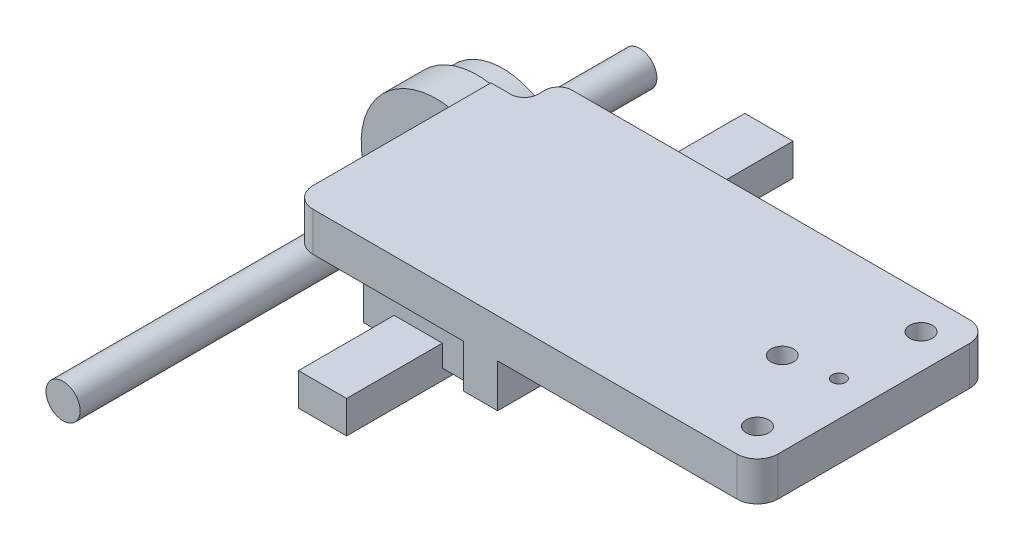
SolidWorks part; units mm, degrees
ref_plane "Front Plane" through (0, 0, 0) normal (0, 0, 1) x (1, 0, 0)
ref_plane "Top Plane" through (0, 0, 0) normal (0, 1, 0) x (1, 0, 0)
ref_plane "Right Plane" through (0, 0, 0) normal (1, 0, 0) x (0, 0, -1)
sketch "Sketch1" plane through (0, 0, 0) normal (0, 1, 0) x (1, 0, 0)
  line L0 (-36.9824, 21.6027) -> (-36.9824, -21.6027)
  line L1 (-43.18, 21.6027) -> (39.37, 21.6027)
  line L2 (-43.18, 21.6027) -> (-43.18, -17.7927)
  line L3 (-39.37, -21.6027) -> (39.37, -21.6027)
  line L4 (43.18, 17.7927) -> (43.18, -17.7927)
  line L5 (-43.18, 21.6027) -> (43.18, -21.6027) construction
  line L6 (-43.18, -21.6027) -> (43.18, 21.6027) construction
  line L7 (-43.18, 15.2527) -> (-36.9824, 15.2527)
  arc A0 (-39.37, -21.6027) -> (-43.18, -17.7927) centre (-39.37, -17.7927) cw
  arc A1 (43.18, -17.7927) -> (39.37, -21.6027) centre (39.37, -17.7927) cw
  arc A2 (39.37, 21.6027) -> (43.18, 17.7927) centre (39.37, 17.7927) cw
  point P1 (0, 0)
  dimension "D3" = 3.81
  dimension "D1" = 43.2054
  dimension "D2" = 86.36
  dimension "D4" = 80.1624
  dimension "D5" = 6.35
extrude "Boss-Extrude1" add sketch "Sketch1" along normal blind 7.2517 contours A2 L1 L0 L3 A1 L4 | A0 L3 L0 L7 L2
fillet "Fillet1" radius 2.54 2 edges at (-36.9824, 3.6258, -15.2527) (-36.9824, 3.6258, -21.6027)
sketch "Sketch3" plane through (0, 0, 0) normal (0, -1, 0) x (1, 0, 0)
  line L0 (-34.4424, -21.6027) -> (39.37, -21.6027) construction
  line L1 (-5.08, -21.6027) -> (-11.4046, -21.6027)
  line L2 (-5.08, -21.6027) -> (-5.08, 21.6027)
  line L3 (-5.08, 21.6027) -> (-11.4046, 21.6027)
  line L4 (-11.4046, -21.6027) -> (-11.4046, 21.6027)
  line L5 (-39.37, 21.6027) -> (39.37, 21.6027) construction
  line L6 (43.18, -17.7927) -> (43.18, 17.7927) construction
  dimension "D1" = 48.26
  dimension "D2" = 6.3246
extrude "Boss-Extrude2" add sketch "Sketch3" along normal blind 8.0264
sketch "Sketch4" plane through (0, 0, 0) normal (0, -1, 0) x (1, 0, 0)
  line L0 (43.18, 0) -> (-43.18, 0) construction
  line L1 (43.18, -17.7927) -> (43.18, 17.7927) construction
  line L2 (-43.18, -15.2527) -> (-43.18, 17.7927) construction
  line L3 (-11.4046, 21.6027) -> (-11.4046, -21.6027) construction
  line L4 (-31.7246, 19.8628) -> (-11.4046, 19.8628)
  line L5 (-31.7246, 19.8628) -> (-31.7246, -19.8628)
  line L6 (-31.7246, -19.8628) -> (-11.4046, -19.8628)
  line L7 (-11.4046, 19.8628) -> (-11.4046, -19.8628)
  line L8 (-31.7246, 19.8628) -> (-11.4046, -19.8628) construction
  line L9 (-31.7246, -19.8628) -> (-11.4046, 19.8628) construction
  point P7 (-21.5646, 0)
  dimension "D1" = 39.7256
  dimension "D2" = 20.32
extrude "Boss-Extrude3" add sketch "Sketch4" along normal blind 8.0264
sketch "Sketch5" plane through (0, -8.0264, 0) normal (0, -1, 0) x (1, 0, 0)
  line L0 (-21.5646, -19.8628) -> (-21.5646, 19.8628) construction
  line L1 (-31.7246, -19.8628) -> (-11.4046, -19.8628) construction
  line L2 (-11.4046, 19.8628) -> (-31.7246, 19.8628) construction
  line L4 (-17.0879, 19.8628) -> (-26.0414, 19.8628)
  line L5 (-17.0879, 19.8628) -> (-17.0879, -19.8628)
  line L6 (-17.0879, -19.8628) -> (-26.0414, -19.8628)
  line L7 (-26.0414, 19.8628) -> (-26.0414, -19.8628)
  line L8 (-17.0879, 19.8628) -> (-26.0414, -19.8628) construction
  line L9 (-17.0879, -19.8628) -> (-26.0414, 19.8628) construction
  point P6 (-21.5646, 0)
  dimension "D1" = 8.9535
extrude "Boss-Extrude4" add sketch "Sketch5" along normal blind 2.032
sketch "Sketch6" plane through (0, 0, -15.2527) normal (0, 0, -1) x (-1, 0, 0)
  line L0 (31.7246, -8.0264) -> (31.7246, 0) construction
  line L5 (43.18, 7.2517) -> (39.5224, 7.2517) construction
  line L6 (31.7246, -6.7183) -> (31.7246, 0)
  line L7 (31.7246, 0) -> (33.4461, 0)
  circle A0 centre (45.6946, -6.7183) radius 13.97
  line M2 (39.5224, 7.2517) -> (39.5224, 0)
  line M3 (39.5224, 0) -> (43.18, 0)
  line M4 (43.18, 0) -> (43.18, 7.2517)
  dimension "D1" = 27.94
  dimension "D2" = 13.97
  dimension "D3" = 13.97
extrude "Boss-Extrude5" add sketch "Sketch6" against normal blind 7.62 contours A0 L7 L6 | A0 M2 M4 M3
sketch "Sketch7" plane through (0, 0, -15.2527) normal (0, 0, -1) x (-1, 0, 0)
  circle A0 centre (45.6946, -6.7183) radius 12.6365
  dimension "D1" = 25.273
extrude "Boss-Extrude6" add sketch "Sketch7" along normal blind 4.7625
sketch "Sketch8" plane through (0, 0, -7.6327) normal (0, 0, 1) x (1, 0, 0)
  circle A0 centre (-45.6946, -6.7183) radius 6.35
  dimension "D1" = 12.7
extrude "Boss-Extrude7" add sketch "Sketch8" along normal blind 12.7
sketch "Sketch10" plane through (0, 0, 5.0673) normal (0, 0, 1) x (1, 0, 0)
  circle A0 centre (-45.6946, -6.7183) radius 3.175
  dimension "D1" = 6.35
extrude "Boss-Extrude8" add sketch "Sketch10" along normal blind 56.642
sketch "Sketch12" plane through (0, 0, -20.0152) normal (0, 0, -1) x (-1, 0, 0)
  circle A0 centre (45.6946, -6.7183) radius 3.175
  dimension "D1" = 6.35
extrude "Boss-Extrude9" add sketch "Sketch12" along normal blind 25.4
sketch "Sketch14" plane through (0, 0, -19.8628) normal (0, 0, -1) x (-1, 0, 0)
  line L0 (26.0414, -10.0584) -> (26.0414, -8.0264) construction
  line L1 (17.0879, -10.0584) -> (26.0414, -10.0584)
  line L2 (17.0879, -10.0584) -> (17.0879, -4.0894)
  line L3 (17.0879, -4.0894) -> (26.0414, -4.0894)
  line L4 (26.0414, -10.0584) -> (26.0414, -4.0894)
  dimension "D1" = 5.969
sketch "Sketch15" plane through (0, 0, 19.8628) normal (0, 0, 1) x (1, 0, 0)
  line L0 (-17.0879, -10.0584) -> (-17.0879, -8.0264) construction
  line L1 (-26.0414, -10.0584) -> (-17.0879, -10.0584)
  line L2 (-26.0414, -10.0584) -> (-26.0414, -4.0192)
  line L3 (-26.0414, -4.0192) -> (-17.0879, -4.0192)
  line L4 (-17.0879, -10.0584) -> (-17.0879, -4.0192)
  dimension "D1" = 6.0392
extrude "Boss-Extrude12" add sketch "Sketch15" along normal blind 17.78
extrude "Boss-Extrude13" add sketch "Sketch14" along normal blind 25.4
sketch "Sketch16" plane through (0, 7.2517, 0) normal (0, 1, 0) x (1, 0, 0)
  line L2 (43.18, 17.7927) -> (43.18, -17.7927) construction
  line L3 (-34.4424, 21.6027) -> (39.37, 21.6027) construction
  line L4 (-39.37, -21.6027) -> (39.37, -21.6027) construction
  circle A0 centre (36.8046, 15.1511) radius 2.286
  circle A1 centre (36.83, -15.2527) radius 2.286
  circle A2 centre (36.703, 0) radius 1.778
  circle A3 centre (27.7241, -1.5367) radius 3.1115
  dimension "D1" = 4.572
  dimension "D2" = 6.3754
  dimension "D3" = 6.4516
  dimension "D4" = 4.572
  dimension "D5" = 6.35
  dimension "D6" = 6.35
  dimension "D7" = 0
  dimension "D8" = 6.477
  dimension "D9" = 3.556
  dimension "D10" = 6.223
  dimension "D11" = 15.4559
hole_wizard "Tap Drill for M5x0.8 Tap1" positions "Sketch19" profile "Sketch20" hole size "M5x0.8" standard "ANSI Metric"
sketch "Sketch19" plane through (0, 7.2517, 0) normal (0, 1, 0) x (1, 0, 0)
  point P0 (36.8046, 15.1511)
  point P3 (36.83, -15.2527)
sketch "Sketch20" plane through (36.8046, 7.2517, -15.1511) normal (1, 0, 0) x (0, 0, 1)
  line L0 (0, 0) -> (0, 26.6618)
  line L1 (0, 26.6618) -> (2.1, 25.4)
  line L2 (2.1, 25.4) -> (2.1, 0)
  line L5 (2.1, 0) -> (0, 0)
  line L10 (0, 26.6618) -> (-2.1, 25.4) construction
  line L11 (0, -6.35) -> (0, 107.95) construction
  dimension "Hole Dia." = 4.2
  dimension "Hole Depth" = 25.4
  dimension "Drill Angle" = 118
hole_wizard "Tap Drill for M3x0.5 Tap1" positions "Sketch21" profile "Sketch22" hole size "M3x0.5" standard "ANSI Metric"
sketch "Sketch21" plane through (0, 7.2517, 0) normal (0, 1, 0) x (1, 0, 0)
  point P0 (36.703, 0)
sketch "Sketch22" plane through (36.703, 7.2517, 0) normal (1, 0, 0) x (0, 0, 1)
  line L0 (0, 0) -> (0, 26.1511)
  line L1 (0, 26.1511) -> (1.25, 25.4)
  line L2 (1.25, 25.4) -> (1.25, 0)
  line L5 (1.25, 0) -> (0, 0)
  line L10 (0, 26.1511) -> (-1.25, 25.4) construction
  line L11 (0, -6.35) -> (0, 107.95) construction
  dimension "Hole Dia." = 2.5
  dimension "Hole Depth" = 25.4
  dimension "Drill Angle" = 118
hole_wizard "Tap Drill for M5x0.8 Tap2" positions "Sketch23" profile "Sketch24" hole size "M5x0.8" standard "ANSI Metric"
sketch "Sketch23" plane through (0, 7.2517, 0) normal (0, 1, 0) x (1, 0, 0)
  point P0 (27.7241, -1.5367)
sketch "Sketch24" plane through (27.7241, 7.2517, 1.5367) normal (1, 0, 0) x (0, 0, 1)
  line L0 (0, 0) -> (0, 26.6618)
  line L1 (0, 26.6618) -> (2.1, 25.4)
  line L2 (2.1, 25.4) -> (2.1, 0)
  line L5 (2.1, 0) -> (0, 0)
  line L10 (0, 26.6618) -> (-2.1, 25.4) construction
  line L11 (0, -6.35) -> (0, 107.95) construction
  dimension "Hole Dia." = 4.2
  dimension "Hole Depth" = 25.4
  dimension "Drill Angle" = 118
